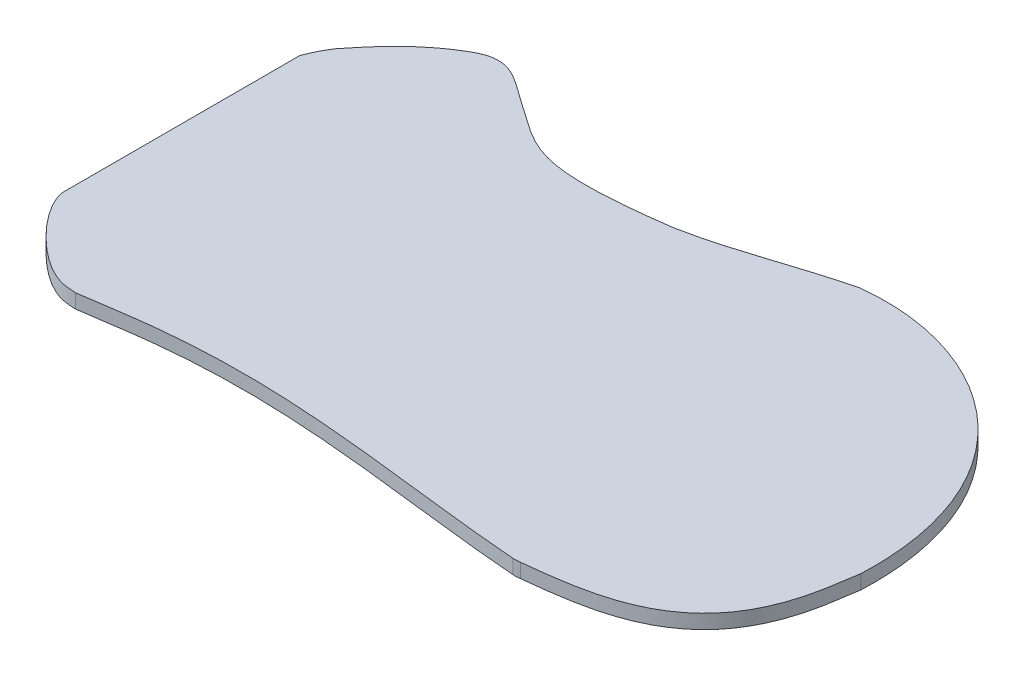
SolidWorks part; units mm, degrees
ref_plane "Front Plane" through (0, 0, 0) normal (0, 0, 1) x (1, 0, 0)
ref_plane "Top Plane" through (0, 0, 0) normal (0, 1, 0) x (1, 0, 0)
ref_plane "Right Plane" through (0, 0, 0) normal (1, 0, 0) x (0, 0, -1)
sketch "Sketch1" plane through (0, 0, 0) normal (0, 1, 0) x (1, 0, 0)
  line L0 (-78.6109, 24.9032) -> (-78.6109, -25.142)
  line L1 (78.526, -10.9955) -> (-78.6109, -10.9955) construction
  line L2 (-77.6109, 24.7348) -> (-77.6109, -25.142)
  line L3 (78.526, -11.9955) -> (-78.6109, -11.9955)
  arc A0 (37.4157, -46.3273) -> (39.1437, -46.2432) centre (37.8097, -36.6353) ccw
  arc A1 (37.4725, -45.3288) -> (39.0215, -45.2505) centre (37.8097, -36.6353) ccw
  spline S0 degree 3 poles (-77.6109, -25.142) (-77.6103, -25.4) (-77.563, -25.903) (-77.2897, -26.9857) (-76.6417, -28.5306) (-75.4978, -30.4481) (-73.6058, -33.039) (-70.8033, -36.112) (-67.3274, -39.127) (-64.1402, -41.244) (-61.4556, -42.4361) (-59.2812, -42.8778) (-58.0256, -42.9092) (-57.3728, -42.9466) knots 0.000484 0.000484 0.000484 0.000484 0.031521 0.062558 0.124632 0.186706 0.248781 0.372929 0.497077 0.621225 0.745373 0.869521 0.993669 0.993669 0.993669 0.993669
  spline S1 degree 3 poles (-57.3728, -42.9466) (-57.1306, -42.9172) (-56.6559, -42.8572) (-55.6329, -42.7168) (-54.2832, -42.5176) (-52.5297, -42.2482) (-50.0282, -41.8652) (-46.6003, -41.367) (-42.0363, -40.8111) (-37.0514, -40.3559) (-29.8812, -39.9429) (-20.0109, -39.8766) (-6.9377, -40.6174) (4.791, -41.8163) (14.5692, -42.9593) (22.0672, -43.8389) (29.7001, -44.6718) (34.8871, -45.1373) (37.4725, -45.3288) knots 0.000538 0.000538 0.000538 0.000538 0.016152 0.031766 0.062993 0.094221 0.125449 0.187904 0.250359 0.312815 0.37527 0.50018 0.625091 0.750001 0.812457 0.874912 0.937367 0.999822 0.999822 0.999822 0.999822
  spline S2 degree 3 poles (39.0215, -45.2505) (40.5541, -45.0873) (43.6362, -44.7445) (49.6297, -43.8727) (56.6431, -42.2158) (63.7646, -38.9137) (69.3225, -34.2155) (72.596, -29.3087) (74.4639, -25.0567) (75.5267, -21.803) (76.2971, -18.6022) (76.7457, -16.0939) (77.026, -14.2578) (77.207, -12.9947) (77.3723, -11.8407) (77.4763, -11.2132) (77.5311, -10.8821) knots -0.000309 -0.000309 -0.000309 -0.000309 0.063093 0.126495 0.253299 0.380104 0.506908 0.633712 0.697114 0.760516 0.823918 0.88732 0.919021 0.950722 0.982423 1.014124 1.014124 1.014124 1.014124
  spline S3 degree 3 poles (77.5311, -10.8821) (77.5748, -9.7665) (77.6099, -7.5074) (77.4888, -4.2729) (77.2058, -1.1252) (76.6195, 2.9373) (75.5088, 7.7538) (72.9895, 14.9059) (68.5668, 22.78) (61.5957, 30.4634) (53.3357, 36.3146) (44.1583, 40.2648) (34.4498, 42.2506) (27.8575, 42.2059) (24.6064, 41.8434) knots 0.000169 0.000169 0.000169 0.000169 0.031414 0.062658 0.093902 0.125147 0.187635 0.250124 0.375101 0.500079 0.625056 0.750034 0.875011 0.999988 0.999988 0.999988 0.999988
  spline S4 degree 3 poles (24.6064, 41.8434) (19.4417, 40.5996) (11.8686, 38.1019) (1.7069, 34.9414) (-3.4909, 33.6615) (-6.1131, 33.1605) knots 0.000659 0.000659 0.000659 0.000659 0.498067 0.746772 0.995476 0.995476 0.995476 0.995476
  spline S5 degree 3 poles (-6.1131, 33.1605) (-7.1417, 33.0163) (-9.1825, 32.742) (-13.4171, 32.237) (-18.6364, 31.7654) (-24.3553, 31.6023) (-29.2844, 31.96) (-33.4204, 32.9216) (-36.3715, 34.2616) (-38.6497, 35.6481) (-40.393, 36.836) (-41.9608, 37.95) (-43.3176, 38.8994) (-44.0701, 39.4107) (-44.4391, 39.6587) knots -0.000196 -0.000196 -0.000196 -0.000196 0.062587 0.12537 0.250936 0.376501 0.502067 0.627632 0.753198 0.815981 0.878764 0.941546 0.972938 1.004329 1.004329 1.004329 1.004329
  spline S6 degree 3 poles (-44.4391, 39.6587) (-44.6983, 39.8375) (-45.2219, 40.2027) (-46.2044, 40.9033) (-47.345, 41.7292) (-48.5998, 42.6198) (-50.1509, 43.6513) (-51.9146, 44.6189) (-53.8615, 45.2294) (-55.7055, 45.3275) (-57.1648, 45.051) (-58.2486, 44.6839) (-59.0003, 44.3616) (-59.6837, 44.0129) (-60.0375, 43.8061) (-60.2239, 43.694) knots -0.002497 -0.002497 -0.002497 -0.002497 0.029066 0.060629 0.123754 0.18688 0.250006 0.376257 0.502509 0.62876 0.755012 0.818137 0.881263 0.944389 1.007515 1.007515 1.007515 1.007515
  spline S7 degree 3 poles (-78.6109, -25.142) (-78.6097, -25.7822) (-78.3711, -27.0076) (-77.5216, -29.0127) (-76.3076, -31.0396) (-74.3365, -33.7283) (-71.4439, -36.8883) (-67.8634, -39.9802) (-64.5529, -42.1647) (-61.6917, -43.4202) (-59.6968, -43.8088) (-58.2959, -43.9054) (-57.6656, -43.9305) (-57.3419, -43.9502) knots 0.000409 0.000409 0.000409 0.000409 0.062843 0.125276 0.18771 0.250143 0.375011 0.499878 0.624745 0.749612 0.874479 0.936913 0.999346 0.999346 0.999346 0.999346
  spline S8 degree 3 poles (-57.3419, -43.9502) (-57.0965, -43.9206) (-56.6141, -43.8604) (-55.5847, -43.7202) (-54.2292, -43.5208) (-52.4771, -43.2519) (-49.983, -42.8696) (-46.5727, -42.3725) (-42.0367, -41.817) (-37.0824, -41.3612) (-29.9535, -40.9457) (-20.1287, -40.874) (-7.0907, -41.608) (4.6318, -42.8047) (14.4219, -43.9489) (21.9389, -44.8307) (29.5994, -45.6669) (34.8166, -46.135) (37.4157, -46.3273) knots -0.001373 -0.001373 -0.001373 -0.001373 0.014273 0.029919 0.06121 0.092502 0.123794 0.186377 0.24896 0.311543 0.374127 0.499293 0.62446 0.749626 0.81221 0.874793 0.937376 0.99996 0.99996 0.99996 0.99996
  spline S9 degree 3 poles (39.1437, -46.2432) (40.686, -46.0789) (43.7818, -45.7344) (49.848, -44.8507) (56.9964, -43.16) (64.3453, -39.7462) (70.1244, -34.8409) (73.5118, -29.7304) (75.4294, -25.3355) (76.5134, -21.9918) (77.2941, -18.7213) (77.7459, -16.1748) (78.0266, -14.3264) (78.2075, -13.0606) (78.3702, -11.9307) (78.4738, -11.3105) (78.5279, -10.984) knots -0.000086 -0.000086 -0.000086 -0.000086 0.063428 0.126941 0.253967 0.380993 0.50802 0.635046 0.698559 0.762072 0.825585 0.889098 0.920855 0.952612 0.984368 1.016125 1.016125 1.016125 1.016125
  spline S10 degree 3 poles (78.5279, -10.984) (78.5733, -9.8502) (78.6109, -7.5559) (78.4906, -4.2601) (78.2049, -1.0549) (77.6104, 3.0871) (76.4803, 8.0028) (73.9108, 15.31) (69.3901, 23.3646) (62.2582, 31.2245) (53.8088, 37.2052) (44.4261, 41.2372) (34.4991, 43.2588) (27.7571, 43.2053) (24.4331, 42.8302) knots -0.000407 -0.000407 -0.000407 -0.000407 0.03088 0.062166 0.093453 0.12474 0.187314 0.249888 0.375035 0.500183 0.62533 0.750478 0.875625 1.000773 1.000773 1.000773 1.000773
  spline S11 degree 3 poles (24.4331, 42.8302) (21.8301, 42.2051) (16.6685, 40.7402) (6.525, 37.4536) (-1.0744, 35.1413) (-6.2764, 34.1474) knots -0.001281 -0.001281 -0.001281 -0.001281 0.247714 0.49671 0.9947 0.9947 0.9947 0.9947
  spline S12 degree 3 poles (-6.2764, 34.1474) (-7.3001, 34.0039) (-9.3317, 33.7312) (-13.542, 33.2295) (-18.7181, 32.7628) (-24.3556, 32.604) (-29.1564, 32.9561) (-33.1061, 33.8787) (-35.9015, 35.1472) (-38.1022, 36.4854) (-39.8157, 37.6526) (-41.3786, 38.7631) (-42.7458, 39.7198) (-43.5043, 40.2353) (-43.8763, 40.4853) knots 0.000305 0.000305 0.000305 0.000305 0.063048 0.125791 0.251276 0.376761 0.502247 0.627732 0.753218 0.815961 0.878703 0.941446 0.972817 1.004189 1.004189 1.004189 1.004189
  spline S13 degree 3 poles (-43.8763, 40.4853) (-44.1324, 40.662) (-44.6496, 41.0228) (-45.6222, 41.7163) (-46.7618, 42.5415) (-48.0307, 43.4423) (-49.6264, 44.5037) (-51.4979, 45.535) (-53.6685, 46.2221) (-55.7733, 46.3353) (-57.4106, 46.0235) (-58.6015, 45.6208) (-59.4227, 45.2686) (-60.0246, 44.9622) (-60.4597, 44.7184) (-60.6399, 44.6107) (-60.7341, 44.5541) knots -0.002294 -0.002294 -0.002294 -0.002294 0.029245 0.060783 0.12386 0.186936 0.250013 0.376167 0.50232 0.628473 0.754627 0.817704 0.88078 0.943857 0.975396 1.006934 1.006934 1.006934 1.006934
  spline S14 degree 3 poles (-60.7341, 44.5541) (-61.1687, 44.2998) (-62.0358, 43.7712) (-63.676, 42.6889) (-66.3643, 40.7074) (-69.6969, 37.7112) (-72.4782, 34.663) (-74.193, 32.5981) (-75.1195, 31.4458) (-75.5587, 30.8903) (-75.7803, 30.6092) knots 0.000427 0.000427 0.000427 0.000427 0.063268 0.126109 0.251792 0.503158 0.754524 0.880206 0.943048 1.005889 1.005889 1.005889 1.005889
  spline S15 degree 3 poles (-60.2239, 43.694) (-60.6474, 43.4463) (-61.4924, 42.9314) (-63.0906, 41.8773) (-65.7124, 39.9465) (-68.9709, 37.0199) (-71.6981, 34.0358) (-73.6437, 31.6948) (-74.5236, 30.5881) (-74.9696, 30.0223) knots 0.000174 0.000174 0.000174 0.000174 0.062881 0.125589 0.251004 0.501833 0.752662 0.878077 1.003492 1.003492 1.003492 1.003492
  spline S16 degree 3 poles (-74.9696, 30.0223) (-75.5195, 29.1919) (-76.5302, 27.448) (-77.2874, 25.6577) (-77.6109, 24.7348) knots 0.499549 0.499549 0.499549 0.499549 0.499766 0.499983 0.499983 0.499983 0.499983
  spline S17 degree 3 poles (-75.7803, 30.6092) (-76.3738, 29.7162) (-77.4602, 27.8403) (-78.2688, 25.9015) (-78.6109, 24.9032) knots 0.499546 0.499546 0.499546 0.499546 0.49977 0.499995 0.499995 0.499995 0.499995
  point P0 (0.0094, -10.9955)
extrude "Boss-Extrude2" add sketch "Sketch1" along normal blind 3 contours L1 S2 S3 S4 S5 S6 S15 S16 L2 | S2 L1 L2 L3 | A1 S2 L3 L2 S0 S1
ref_plane "Plane1" through (0, 0, -24.7348) normal (0, 0, -1) x (0, -1, 0)
sketch "Sketch2" plane through (0, 3, 0) normal (0, 1, 0) x (1, 0, 0)
  circle A0 centre (-52.6013, 19.445) radius 6
extrude "Boss-Extrude3" add sketch "Sketch2" along normal blind 2.5
sketch "Sketch4" plane through (0, 5.5, 0) normal (0, 1, 0) x (1, 0, 0)
  circle A0 centre (-52.6013, 19.445) radius 2.5
extrude "Cut-Extrude1" cut sketch "Sketch4" against normal blind 2.5
pattern_linear "LPattern1" count 3 spacing 20 along (0, 0, 1) count 6 spacing 20 along (1, 0, 0) of "Cut-Extrude1", "Boss-Extrude3"
sketch "Sketch5" plane through (0, 0, 0) normal (0, -1, 0) x (1, 0, 0)
  line L0 (-77.1109, 25.142) -> (-77.1109, -24.6492)
  line L1 (-77.6109, 25.142) -> (-77.6109, -24.7348)
  line L2 (-77.6109, 25.142) -> (-77.6109, -24.7348)
  arc A0 (38.96, 44.7543) -> (37.5005, 44.8295) centre (37.8097, 36.6353) ccw
  arc A1 (39.0215, 45.2505) -> (37.4725, 45.3288) centre (37.8097, 36.6353) ccw
  arc A2 (39.0215, 45.2505) -> (37.4725, 45.3288) centre (37.8097, 36.6353) ccw
  spline S0 degree 1 poles (-77.1109, -24.6492) (-74.5641, -29.729) knots 0 0 1 1 construction
  spline S1 degree 1 poles (-74.5641, -29.729) (-59.9689, -43.2639) knots 0 0 1 1 construction
  spline S2 degree 1 poles (-59.9689, -43.2639) (-44.7205, -39.2454) knots 0 0 1 1 construction
  spline S3 degree 1 poles (-44.7205, -39.2454) (-6.0314, -32.6671) knots 0 0 1 1 construction
  spline S4 degree 1 poles (-6.0314, -32.6671) (24.6929, -41.3499) knots 0 0 1 1 construction
  spline S5 degree 1 poles (24.6929, -41.3499) (77.0327, 10.8313) knots 0 0 1 1 construction
  spline S6 degree 1 poles (77.0327, 10.8313) (38.96, 44.7543) knots 0 0 1 1 construction
  spline S7 degree 1 poles (37.5005, 44.8295) (-57.3891, 42.4449) knots 0 0 1 1 construction
  spline S8 degree 1 poles (-57.3891, 42.4449) (-77.1109, 25.142) knots 0 0 1 1 construction
  spline S9 degree 3 poles (-1292.9492, 3779.6378) (100.4819, 121.292) (-270.5174, -52.7097) (123.0243, -86.4476) (-1828.5894, 3561.256) knots 0.486703 0.486703 0.486703 0.486703 0.499766 0.510508 0.510508 0.510508 0.510508 only from (-77.6109, -24.7348) to (-74.9696, -30.0223)
  spline S10 degree 3 poles (-2921.2125, 2780.1724) (-66.526, -13.1931) (-95.7454, -5.102) (-71.6981, -34.0358) (-68.9709, -37.0199) (-65.7124, -39.9465) (-63.0906, -41.8773) (-34.0649, -61.0208) (51.5108, -64.5284) (-3365.7604, 2207.7873) knots -5.69846 -5.69846 -5.69846 -5.69846 0.125589 0.251004 0.501833 0.752662 0.878077 0.940785 5.30832 5.30832 5.30832 5.30832 only from (-74.9696, -30.0223) to (-60.2239, -43.694)
  spline S11 degree 3 poles (-3718.6204, 1573.4481) (-20.9784, -48.1476) (-70.3352, -38.5778) (-59.0003, -44.3616) (-58.2486, -44.6839) (-57.1648, -45.051) (-55.7055, -45.3275) (-53.8615, -45.2294) (-51.9146, -44.6189) (-50.1509, -43.6513) (-48.5998, -42.6198) (-47.345, -41.7292) (-46.2044, -40.9033) (-28.7081, -28.4273) (27.1334, 1.5659) (-3303.9447, -2357.8048) knots -2.954336 -2.954336 -2.954336 -2.954336 0.060629 0.123754 0.18688 0.250006 0.376257 0.502509 0.62876 0.755012 0.818137 0.881263 0.944389 0.975952 3.129527 3.129527 3.129527 3.129527 only from (-60.2239, -43.694) to (-44.4391, -39.6587)
  spline S12 degree 3 poles (3295.5795, 2160.7476) (-129.6645, -88.806) (-60.4957, -50.9183) (-41.9608, -37.95) (-40.393, -36.836) (-38.6497, -35.6481) (-36.3715, -34.2616) (-33.4204, -32.9216) (-29.2844, -31.96) (-24.3553, -31.6023) (-18.6364, -31.7654) (-13.4171, -32.237) (45.4887, -39.2627) (47.2911, -61.6923) (3982.0845, -336.2969) knots -1.5899 -1.5899 -1.5899 -1.5899 0.031196 0.062587 0.12537 0.188153 0.250936 0.376501 0.502067 0.627632 0.753198 0.878764 0.941546 4.246632 4.246632 4.246632 4.246632 only from (-44.4391, -39.6587) to (-6.1131, -33.1605)
  spline S13 degree 3 poles (-80.2032, -4021.3294) (-241.6483, -92.4832) (-94.2898, -5.0854) (109.1158, -68.3468) (204.8413, -125.0806) (1412.9302, 3700.5542) knots -9.397262 -9.397262 -9.397262 -9.397262 0.249363 0.498067 10.515807 10.515807 10.515807 10.515807 only from (-6.1131, -33.1605) to (24.6064, -41.8434)
  spline S14 degree 3 poles (3742.3342, 1311.6694) (-259.6442, 435.0293) (-86.2039, -66.9285) (44.1583, -40.2648) (53.3357, -36.3146) (61.5957, -30.4634) (68.5668, -22.78) (72.9895, -14.9059) (75.5088, -7.7538) (76.6195, -2.9373) (77.2058, 1.1252) (77.4888, 4.2729) (79.4987, 57.9677) (12.5396, 171.7612) (179.7425, -3986.7911) knots -4.659359 -4.659359 -4.659359 -4.659359 0.125147 0.250124 0.375101 0.500079 0.625056 0.750034 0.812522 0.875011 0.906255 0.9375 0.968744 2.462267 2.462267 2.462267 2.462267 only from (24.6064, -41.8434) to (77.5311, 10.8821)
  spline S15 degree 3 poles (421.0309, -3974.0128) (79.0927, 46.9008) (79.6739, -4.2247) (77.207, 12.9947) (77.026, 14.2578) (76.7457, 16.0939) (76.2971, 18.6022) (75.5267, 21.803) (74.4639, 25.0567) (72.596, 29.3087) (69.3225, 34.2155) (63.7646, 38.9137) (56.6431, 42.2158) (49.6297, 43.8727) (-31.1617, 55.6242) (-166.4736, 4.1608) (3582.0399, 1899.5244) knots -1.324215 -1.324215 -1.324215 -1.324215 0.031392 0.063093 0.094794 0.126495 0.189897 0.253299 0.316701 0.380104 0.506908 0.633712 0.760516 0.88732 0.950722 4.179081 4.179081 4.179081 4.179081 only from (77.5311, 10.8821) to (39.0215, 45.2505)
  spline S16 degree 3 poles (-3218.5846, -2265.7483) (339.1617, 16.0622) (151.349, 57.9473) (22.0672, 43.8389) (14.5692, 42.9593) (4.791, 41.8163) (-6.9377, 40.6174) (-20.0109, 39.8766) (-29.8812, 39.9429) (-37.0514, 40.3559) (-42.0363, 40.8111) (-46.6003, 41.367) (-50.0282, 41.8652) (-52.5297, 42.2482) (-54.2832, 42.5176) (-55.6329, 42.7168) (-73.2865, 45.1398) (-49.1474, 35.9392) (-4017.1215, 606.7539) knots -2.985626 -2.985626 -2.985626 -2.985626 0.062993 0.125449 0.187904 0.250359 0.37527 0.50018 0.625091 0.687546 0.750001 0.812457 0.874912 0.90614 0.937367 0.968595 0.984209 2.015131 2.015131 2.015131 2.015131 only from (37.4725, 45.3288) to (-57.3728, 42.9466)
  spline S17 degree 3 poles (2561.7663, 3065.6676) (-68.1011, -24.7449) (-35.8645, 47.6353) (-61.4556, 42.4361) (-64.1402, 41.244) (-67.3274, 39.127) (-70.8033, 36.112) (-73.6058, 33.039) (-75.4978, 30.4481) (-76.6417, 28.5306) (-77.2897, 26.9857) (-81.8174, 9.0472) (6.0157, 31.1691) (371.4432, -3948.3099) knots -4.010335 -4.010335 -4.010335 -4.010335 0.124632 0.248781 0.372929 0.497077 0.621225 0.745373 0.807447 0.869521 0.931595 0.962632 2.926447 2.926447 2.926447 2.926447 only from (-57.3728, 42.9466) to (-77.6109, 25.142)
  spline S18 degree 3 poles (-77.6109, -24.7348) (-77.2874, -25.6577) (-76.5302, -27.448) (-75.5195, -29.1919) (-74.9696, -30.0223) knots 0.499549 0.499549 0.499549 0.499549 0.499766 0.499983 0.499983 0.499983 0.499983
  spline S19 degree 3 poles (-74.9696, -30.0223) (-74.5236, -30.5881) (-73.6437, -31.6948) (-71.6981, -34.0358) (-68.9709, -37.0199) (-65.7124, -39.9465) (-63.0906, -41.8773) (-61.4924, -42.9314) (-60.6474, -43.4463) (-60.2239, -43.694) knots 0.000174 0.000174 0.000174 0.000174 0.125589 0.251004 0.501833 0.752662 0.878077 0.940785 1.003492 1.003492 1.003492 1.003492
  spline S20 degree 3 poles (-60.2239, -43.694) (-60.0375, -43.8061) (-59.6837, -44.0129) (-59.0003, -44.3616) (-58.2486, -44.6839) (-57.1648, -45.051) (-55.7055, -45.3275) (-53.8615, -45.2294) (-51.9146, -44.6189) (-50.1509, -43.6513) (-48.5998, -42.6198) (-47.345, -41.7292) (-46.2044, -40.9033) (-45.2219, -40.2027) (-44.6983, -39.8375) (-44.4391, -39.6587) knots -0.002497 -0.002497 -0.002497 -0.002497 0.060629 0.123754 0.18688 0.250006 0.376257 0.502509 0.62876 0.755012 0.818137 0.881263 0.944389 0.975952 1.007515 1.007515 1.007515 1.007515
  spline S21 degree 3 poles (-44.4391, -39.6587) (-44.0701, -39.4107) (-43.3176, -38.8994) (-41.9608, -37.95) (-40.393, -36.836) (-38.6497, -35.6481) (-36.3715, -34.2616) (-33.4204, -32.9216) (-29.2844, -31.96) (-24.3553, -31.6023) (-18.6364, -31.7654) (-13.4171, -32.237) (-9.1825, -32.742) (-7.1417, -33.0163) (-6.1131, -33.1605) knots -0.000196 -0.000196 -0.000196 -0.000196 0.031196 0.062587 0.12537 0.188153 0.250936 0.376501 0.502067 0.627632 0.753198 0.878764 0.941546 1.004329 1.004329 1.004329 1.004329
  spline S22 degree 3 poles (-6.1131, -33.1605) (-3.4909, -33.6615) (1.7069, -34.9414) (11.8686, -38.1019) (19.4417, -40.5996) (24.6064, -41.8434) knots 0.000659 0.000659 0.000659 0.000659 0.249363 0.498067 0.995476 0.995476 0.995476 0.995476
  spline S23 degree 3 poles (24.6064, -41.8434) (27.8575, -42.2059) (34.4498, -42.2506) (44.1583, -40.2648) (53.3357, -36.3146) (61.5957, -30.4634) (68.5668, -22.78) (72.9895, -14.9059) (75.5088, -7.7538) (76.6195, -2.9373) (77.2058, 1.1252) (77.4888, 4.2729) (77.6099, 7.5074) (77.5748, 9.7665) (77.5311, 10.8821) knots 0.000169 0.000169 0.000169 0.000169 0.125147 0.250124 0.375101 0.500079 0.625056 0.750034 0.812522 0.875011 0.906255 0.9375 0.968744 0.999988 0.999988 0.999988 0.999988
  spline S24 degree 3 poles (77.5311, 10.8821) (77.4763, 11.2132) (77.3723, 11.8407) (77.207, 12.9947) (77.026, 14.2578) (76.7457, 16.0939) (76.2971, 18.6022) (75.5267, 21.803) (74.4639, 25.0567) (72.596, 29.3087) (69.3225, 34.2155) (63.7646, 38.9137) (56.6431, 42.2158) (49.6297, 43.8727) (43.6362, 44.7445) (40.5541, 45.0873) (39.0215, 45.2505) knots -0.000309 -0.000309 -0.000309 -0.000309 0.031392 0.063093 0.094794 0.126495 0.189897 0.253299 0.316701 0.380104 0.506908 0.633712 0.760516 0.88732 0.950722 1.014124 1.014124 1.014124 1.014124
  spline S25 degree 3 poles (37.4725, 45.3288) (34.8871, 45.1373) (29.7001, 44.6718) (22.0672, 43.8389) (14.5692, 42.9593) (4.791, 41.8163) (-6.9377, 40.6174) (-20.0109, 39.8766) (-29.8812, 39.9429) (-37.0514, 40.3559) (-42.0363, 40.8111) (-46.6003, 41.367) (-50.0282, 41.8652) (-52.5297, 42.2482) (-54.2832, 42.5176) (-55.6329, 42.7168) (-56.6559, 42.8572) (-57.1306, 42.9172) (-57.3728, 42.9466) knots 0.000538 0.000538 0.000538 0.000538 0.062993 0.125449 0.187904 0.250359 0.37527 0.50018 0.625091 0.687546 0.750001 0.812457 0.874912 0.90614 0.937367 0.968595 0.984209 0.999822 0.999822 0.999822 0.999822
  spline S26 degree 3 poles (-57.3728, 42.9466) (-58.0256, 42.9092) (-59.2812, 42.8778) (-61.4556, 42.4361) (-64.1402, 41.244) (-67.3274, 39.127) (-70.8033, 36.112) (-73.6058, 33.039) (-75.4978, 30.4481) (-76.6417, 28.5306) (-77.2897, 26.9857) (-77.563, 25.903) (-77.6103, 25.4) (-77.6109, 25.142) knots 0.000484 0.000484 0.000484 0.000484 0.124632 0.248781 0.372929 0.497077 0.621225 0.745373 0.807447 0.869521 0.931595 0.962632 0.993669 0.993669 0.993669 0.993669
  spline S27 degree 3 poles (-77.1109, -24.6492) (-76.7968, -25.5347) (-76.0655, -27.2515) (-75.0924, -28.9297) (-74.5641, -29.729) knots 0.499555 0.499555 0.499555 0.499555 0.499768 0.499981 0.499981 0.499981 0.499981
  spline S28 degree 3 poles (-74.5641, -29.729) (-74.12, -30.2922) (-73.2433, -31.3948) (-71.31, -33.7197) (-68.6075, -36.6748) (-65.3868, -39.5658) (-62.7979, -41.4715) (-61.2209, -42.5114) (-60.3868, -43.0195) (-59.9689, -43.2639) knots 0.001381 0.001381 0.001381 0.001381 0.126661 0.251941 0.502501 0.753061 0.878341 0.940981 1.003621 1.003621 1.003621 1.003621
  spline S29 degree 3 poles (-59.9689, -43.2639) (-59.7887, -43.3723) (-59.4456, -43.573) (-58.5725, -44.0187) (-57.3166, -44.5126) (-55.6706, -44.8238) (-53.9579, -44.733) (-52.1231, -44.161) (-50.4131, -43.225) (-48.8844, -42.2086) (-47.6367, -41.3231) (-46.4956, -40.4968) (-45.5081, -39.7926) (-44.9812, -39.4252) (-44.7205, -39.2454) knots -0.002791 -0.002791 -0.002791 -0.002791 0.060359 0.12351 0.249811 0.376111 0.502412 0.628713 0.755014 0.818164 0.881314 0.944465 0.97604 1.007615 1.007615 1.007615 1.007615
  spline S30 degree 3 poles (-44.7205, -39.2454) (-44.353, -38.9984) (-43.6035, -38.4891) (-42.2518, -37.5435) (-40.6816, -36.4277) (-38.9235, -35.2295) (-36.6064, -33.8187) (-33.5775, -32.443) (-29.3483, -31.462) (-24.3549, -31.1015) (-18.5955, -31.2666) (-13.3546, -31.7407) (-9.1079, -32.2474) (-7.0625, -32.5225) (-6.0314, -32.6671) knots -0.000266 -0.000266 -0.000266 -0.000266 0.031135 0.062536 0.125339 0.188142 0.250945 0.37655 0.502156 0.627762 0.753367 0.878973 0.941776 1.004579 1.004579 1.004579 1.004579
  spline S31 degree 3 poles (-6.0314, -32.6671) (-3.3973, -33.1703) (1.8292, -34.4558) (12.0094, -37.6217) (19.5431, -40.1079) (24.6929, -41.3499) knots 0.000275 0.000275 0.000275 0.000275 0.248829 0.497383 0.99449 0.99449 0.99449 0.99449
  spline S32 degree 3 poles (24.6929, -41.3499) (27.9075, -41.7061) (34.4251, -41.7465) (44.0244, -39.7786) (53.0992, -35.8692) (61.2645, -30.0828) (68.1552, -22.4876) (72.529, -14.7037) (75.0231, -7.629) (76.1241, -2.8621) (76.7062, 1.1605) (76.9879, 4.2795) (77.1094, 7.4833) (77.0756, 9.7248) (77.0327, 10.8313) knots 0.000572 0.000572 0.000572 0.000572 0.125463 0.250353 0.375243 0.500134 0.625024 0.749914 0.81236 0.874805 0.906027 0.93725 0.968472 0.999695 0.999695 0.999695 0.999695
  spline S33 degree 3 poles (77.0327, 10.8313) (76.9775, 11.1648) (76.8733, 11.7961) (76.7067, 12.9618) (76.5258, 14.2226) (76.2458, 16.0523) (75.7988, 18.5411) (75.0338, 21.7069) (73.9818, 24.9154) (72.139, 29.0959) (68.9229, 33.9013) (63.4756, 38.4966) (56.4671, 41.7435) (49.5207, 43.3837) (43.5632, 44.2496) (40.4878, 44.5915) (38.96, 44.7543) knots 0.000679 0.000679 0.000679 0.000679 0.032353 0.064027 0.095701 0.127375 0.190722 0.25407 0.317417 0.380765 0.50746 0.634155 0.76085 0.887546 0.950893 1.014241 1.014241 1.014241 1.014241
  spline S34 degree 3 poles (37.5005, 44.8295) (34.9219, 44.6384) (29.75, 44.1742) (19.5916, 43.0658) (7.2172, 41.5622) (-6.8614, 40.122) (-19.9518, 39.378) (-29.8447, 39.4415) (-37.0354, 39.8533) (-42.0355, 40.3082) (-46.6136, 40.8643) (-50.0505, 41.363) (-52.5558, 41.7463) (-54.3104, 42.016) (-55.6573, 42.2152) (-56.6777, 42.3557) (-57.1485, 42.4155) (-57.3891, 42.4449) knots 0.00061 0.00061 0.00061 0.00061 0.063001 0.125392 0.250174 0.374957 0.499739 0.624521 0.686912 0.749303 0.811694 0.874085 0.905281 0.936477 0.967672 0.98327 0.998868 0.998868 0.998868 0.998868
  spline S35 degree 3 poles (-57.3891, 42.4449) (-57.7105, 42.4269) (-58.3596, 42.3997) (-59.6104, 42.3022) (-61.3317, 41.946) (-63.9306, 40.7854) (-67.0572, 38.702) (-70.4814, 35.7254) (-73.2391, 32.696) (-75.0919, 30.1538) (-76.2008, 28.2911) (-76.8193, 26.8097) (-77.0694, 25.8098) (-77.1103, 25.3707) (-77.1109, 25.142) knots 0.003287 0.003287 0.003287 0.003287 0.065183 0.127078 0.250869 0.374661 0.498452 0.622243 0.746034 0.80793 0.869826 0.931721 0.962669 0.993617 0.993617 0.993617 0.993617
  dimension "D1" = 0
  dimension "D2" = 0.5
extrude "Cut-Extrude2" cut sketch "Sketch5" against normal blind 10
ref_plane "Plane2" through (0, 0, 0) normal (0, -1, 0) x (-1, 0, 0)
mirror "Mirror1" about plane through (0, 0, 0) normal (0, -1, 0) of "Cut-Extrude2", "LPattern1", "Cut-Extrude1", "Boss-Extrude3", "Boss-Extrude2"
sketch "Sketch6" plane through (0, 0, 0) normal (0, -1, 0) x (-1, 0, 0)
  line L1 (-102.8282, 87.4799) -> (117.5884, 87.4799)
  line L2 (-102.8282, 87.4799) -> (-102.8282, -126.8771)
  line L3 (-102.8282, -126.8771) -> (117.5884, -126.8771)
  line L4 (117.5884, 87.4799) -> (117.5884, -126.8771)
extrude "Cut-Extrude3" cut sketch "Sketch6" against normal blind 10
